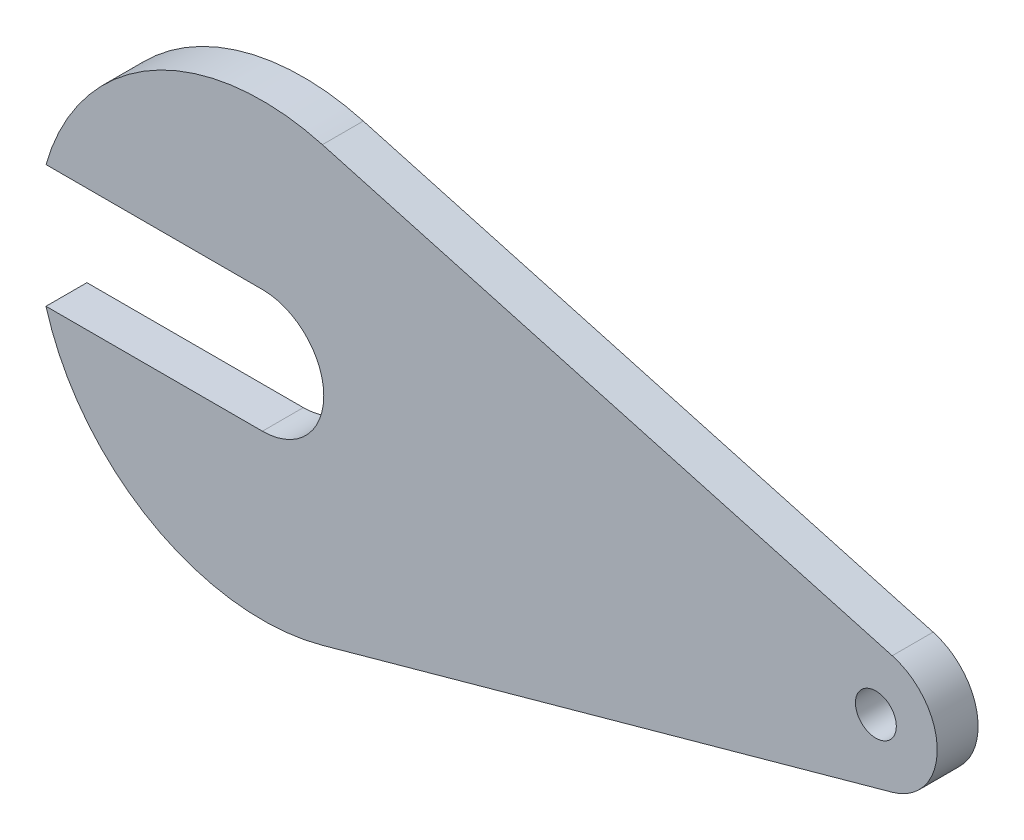
SolidWorks part; units mm, degrees
ref_plane "Alzado" through (0, 0, 0) normal (0, 0, 1) x (1, 0, 0)
ref_plane "Planta" through (0, 0, 0) normal (0, 1, 0) x (1, 0, 0)
ref_plane "Vista lateral" through (0, 0, 0) normal (1, 0, 0) x (0, 0, -1)
sketch "Model" plane through (0, 0, 0) normal (0, 0, 1) x (1, 0, 0)
  line L0 (220.1478, 226.0495) -> (261.9478, 237.615)
  line L1 (261.9478, 246.2891) -> (220.1478, 257.8545)
  line L2 (215.7478, 246.452) -> (199.8733, 246.452)
  line L3 (215.7478, 237.452) -> (199.8733, 237.452)
  arc A0 (199.8733, 237.452) -> (220.1478, 226.0495) centre (215.7478, 241.952) ccw
  arc A1 (220.1478, 257.8545) -> (199.8733, 246.452) centre (215.7478, 241.952) ccw
  arc A2 (261.9478, 237.615) -> (261.9478, 246.2891) centre (260.7478, 241.952) ccw
  arc A3 (215.7478, 237.452) -> (215.7478, 246.452) centre (215.7478, 241.952) ccw
  circle A4 centre (260.7478, 241.952) radius 1.5
extrude "Saliente-Extruir1" add sketch "Model" along normal blind 3
